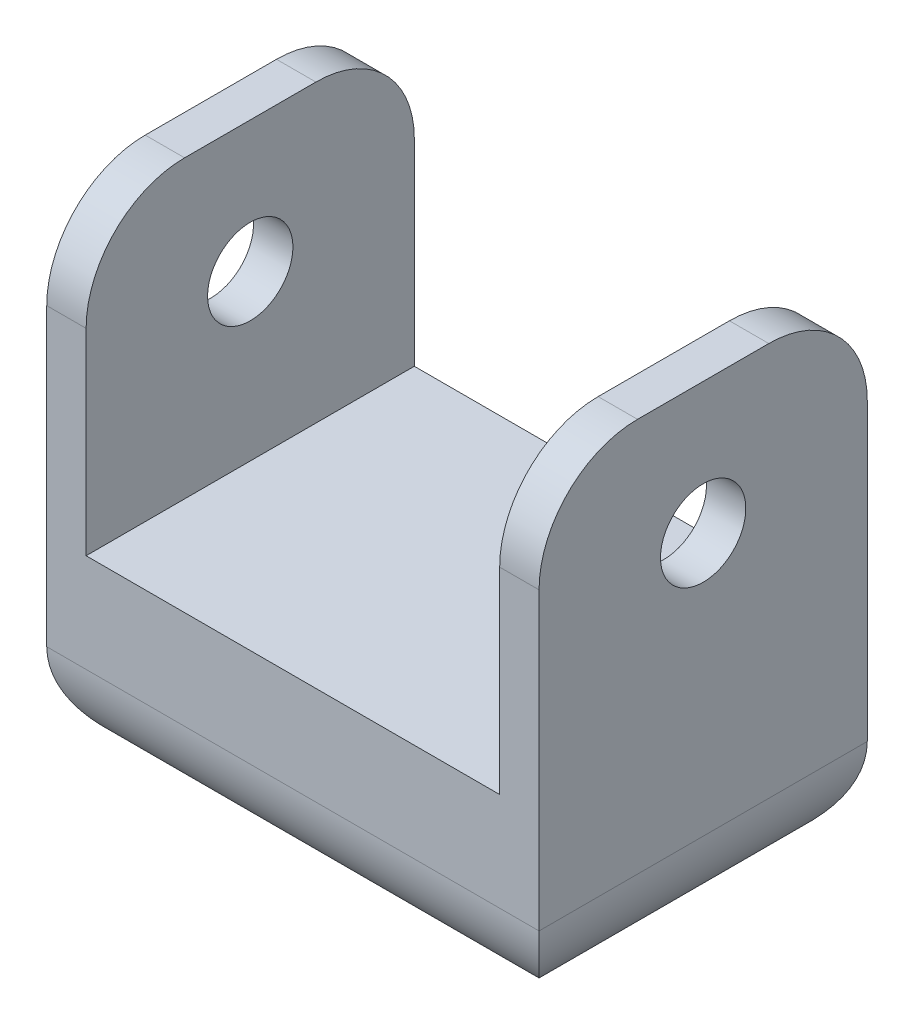
SolidWorks part; units mm, degrees
ref_plane "Front Plane" through (0, 0, 0) normal (0, 0, 1) x (1, 0, 0)
ref_plane "Top Plane" through (0, 0, 0) normal (0, 1, 0) x (1, 0, 0)
ref_plane "Right Plane" through (0, 0, 0) normal (1, 0, 0) x (0, 0, -1)
sketch "Sketch1" plane through (0, 0, 0) normal (0, 1, 0) x (1, 0, 0)
  line L1 (-19.05, 12.7) -> (19.05, 12.7)
  line L2 (-19.05, 12.7) -> (-19.05, -12.7)
  line L3 (-19.05, -12.7) -> (19.05, -12.7)
  line L4 (19.05, 12.7) -> (19.05, -12.7)
  line L5 (-19.05, 12.7) -> (19.05, -12.7) construction
  line L6 (-19.05, -12.7) -> (19.05, 12.7) construction
  point P0 (0, 0)
  dimension "D1" = 38.1
  dimension "D2" = 25.4
extrude "Boss-Extrude1" add sketch "Sketch1" along normal blind 25.4
sketch "Sketch2" plane through (0, 25.4, 0) normal (0, 1, 0) x (1, 0, 0)
  line L0 (19.05, 12.7) -> (-19.05, 12.7) construction
  line L1 (-16.002, 12.7) -> (16.002, 12.7)
  line L2 (-16.002, 12.7) -> (-16.002, -12.7)
  line L3 (-16.002, -12.7) -> (16.002, -12.7)
  line L4 (16.002, 12.7) -> (16.002, -12.7)
  line L5 (-19.05, -12.7) -> (19.05, -12.7) construction
  dimension "D1" = 32.004
  dimension "D2" = 16.002
extrude "Cut-Extrude1" cut sketch "Sketch2" against normal blind 22.86
sketch "Sketch3" plane through (-19.05, 0, 0) normal (-1, 0, 0) x (0, 0, 1)
  line L0 (-12.7, 0) -> (12.7, 0) construction
  circle A0 centre (0, 15.24) radius 3.302
  point P4 (0, 15.24)
  dimension "D1" = 6.604
  dimension "D2" = 15.24
extrude "Cut-Extrude2" cut sketch "Sketch3" against normal through all
fillet "Fillet1" radius 7.62 4 edges at (17.526, 25.4, 12.7) (17.526, 25.4, -12.7) (-17.526, 25.4, 12.7) (-17.526, 25.4, -12.7)
sketch "Sketch4" plane through (0, 0, 0) normal (0, -1, 0) x (1, 0, 0)
  line L1 (-19.05, 12.7) -> (19.05, 12.7)
  line L2 (-19.05, 12.7) -> (-19.05, -12.7)
  line L3 (-19.05, -12.7) -> (19.05, -12.7)
  line L4 (19.05, 12.7) -> (19.05, -12.7)
extrude "Boss-Extrude2" add sketch "Sketch4" along normal blind 12.7
fillet "Fillet2" radius 7.62 4 edges at (0, -12.7, 12.7) (19.05, -12.7, 0) (0, -12.7, -12.7) (-19.05, -12.7, 0)
